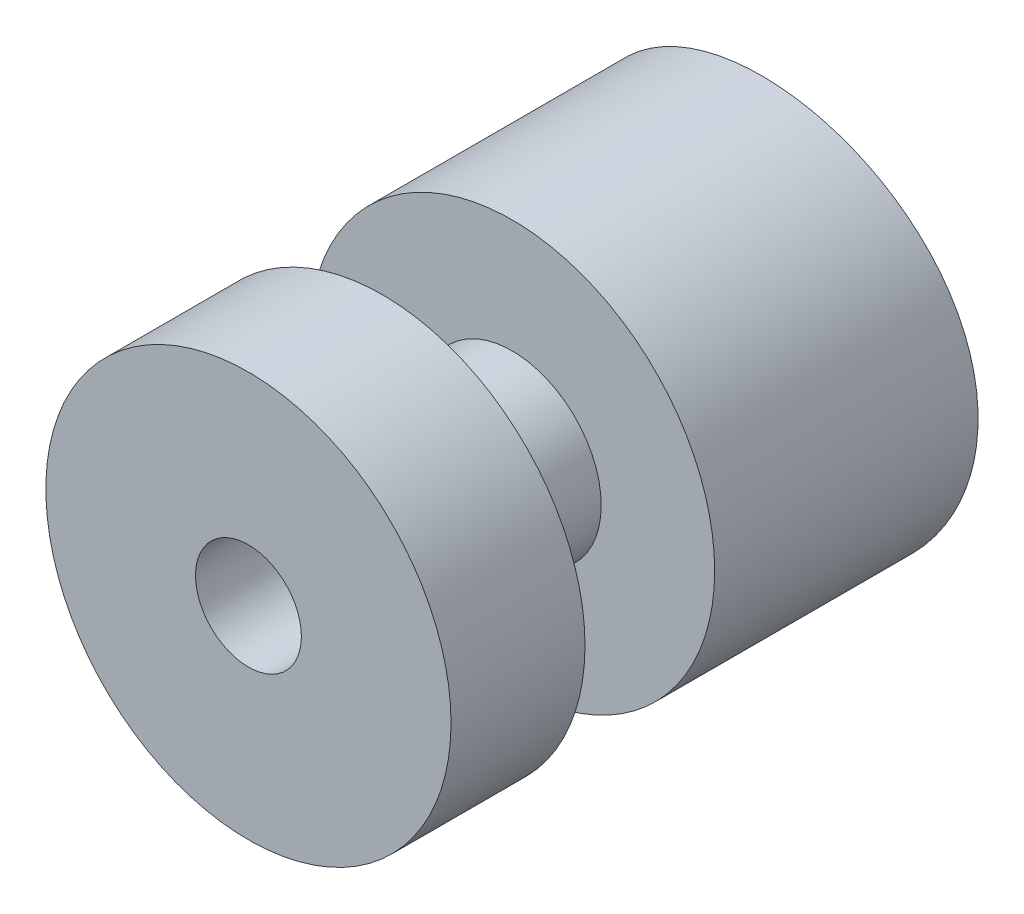
SolidWorks part; units mm, degrees
ref_plane "Front Plane" through (0, 0, 0) normal (0, 0, 1) x (1, 0, 0)
ref_plane "Top Plane" through (0, 0, 0) normal (0, 1, 0) x (1, 0, 0)
ref_plane "Right Plane" through (0, 0, 0) normal (1, 0, 0) x (0, 0, -1)
sketch "Sketch1" plane through (0, 0, 0) normal (0, 0, 1) x (1, 0, 0)
  circle A0 centre (0, 0) radius 9.525
  dimension "D1" = 19.05
extrude "Extrude1" add sketch "Sketch1" along normal blind 24.7828
ref_plane "Plane1" through (0, 0, 18.4836) normal (0, 0, 1) x (1, 0, 0)
sketch "Sketch2" plane through (0, 0, 18.4836) normal (0, 0, 1) x (1, 0, 0)
  circle A0 centre (0, 0) radius 4.191
  dimension "D1" = 8.382
extrude "Extrude2" cut sketch "Sketch2" against normal blind 6.096 flip side to cut
sketch "Sketch3" plane through (0, 0, 0) normal (0, 1, 0) x (1, 0, 0)
  arc A0 (9.525, 0) -> (-9.525, 0) centre (0, 69.1975) cw
  dimension "D1" = 69.85
extrude "Extrude3" cut sketch "Sketch3" against normal through all and the other way through all flip side to cut
hole_wizard "#10 Clearance Hole1" positions "Sketch5" profile "Sketch6" hole size "#10" standard "Ansi Inch" end condition through all
sketch "Sketch5" plane through (0, 0, 24.7828) normal (0, 0, 1) x (1, 0, 0)
  point P1 (0, 0)
sketch "Sketch6" plane through (0, 0, 24.7828) normal (1, 0, 0) x (0, -1, 0)
  line L0 (0, 0) -> (0, 24.7828)
  line L1 (0, 24.7828) -> (2.4892, 24.7828)
  line L2 (2.4892, 24.7828) -> (2.4892, 0)
  line L5 (2.4892, 0) -> (0, 0)
  line L11 (0, -6.35) -> (0, 107.95) construction
  dimension "Thru Hole Dia." = 4.9784
  dimension "Thru Hole Depth" = 24.7828
